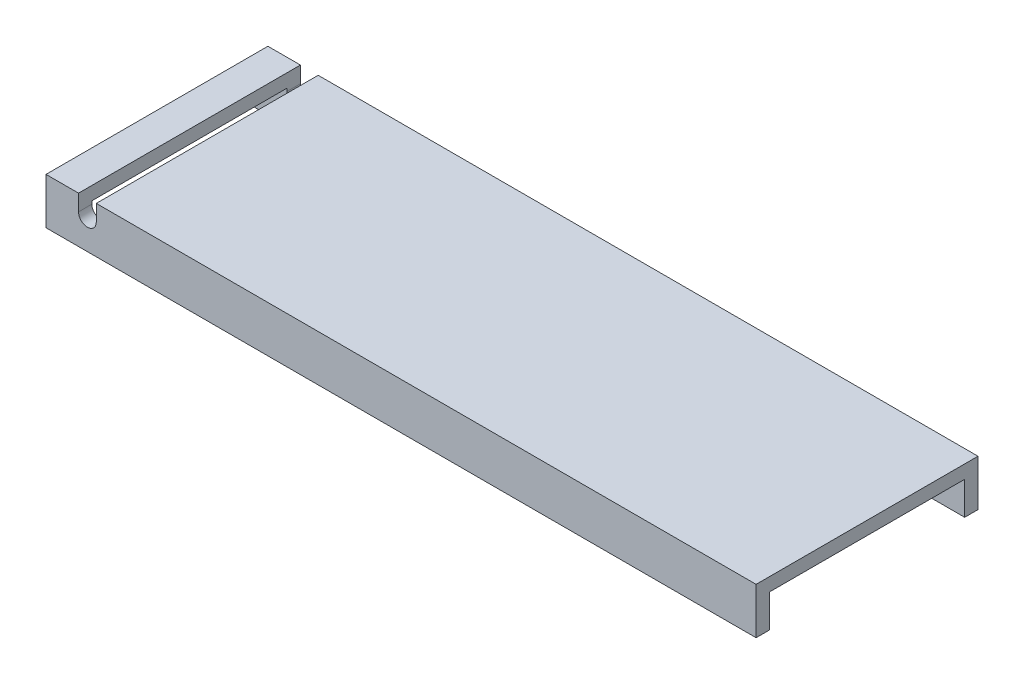
SolidWorks part; units mm, degrees
ref_plane "前视基准面" through (0, 0, 0) normal (0, 0, 1) x (1, 0, 0)
ref_plane "上视基准面" through (0, 0, 0) normal (0, 1, 0) x (1, 0, 0)
ref_plane "右视基准面" through (0, 0, 0) normal (1, 0, 0) x (0, 0, -1)
other "Configuration Table"
sketch "草图1" plane through (0, 0, 0) normal (1, 0, 0) x (0, 0, -1)
  line L0 (-11.391, 5.2124) -> (-11.391, -5.6876)
  line L1 (-9.891, 3.7124) -> (12.109, 3.7124)
  line L2 (-9.891, 3.7124) -> (-9.891, -4.1876)
  line L3 (-9.891, -4.1876) -> (12.109, -4.1876)
  line L4 (12.109, 3.7124) -> (12.109, -4.1876)
  line L5 (-9.891, 3.7124) -> (12.109, -4.1876) construction
  line L6 (-9.891, -4.1876) -> (12.109, 3.7124) construction
  line L7 (-11.391, -5.6876) -> (13.609, -5.6876)
  line L8 (13.609, 5.2124) -> (13.609, -5.6876)
  line L9 (-11.391, 5.2124) -> (13.609, 5.2124)
  point P0 (1.109, -0.2376)
  dimension "D1" = 7.9
  dimension "D2" = 22
  dimension "D3" = 1.5
extrude "凸台-拉伸1" add sketch "草图1" along normal blind 80
sketch "草图3" plane through (0, 0, 11.391) normal (0, 0, 1) x (1, 0, 0)
  line L0 (3.6643, 3.3873) -> (3.6643, 5.2124)
  line L1 (80, 5.2124) -> (0, 5.2124) construction
  line L2 (5.6643, 3.3873) -> (5.6643, 5.2124)
  line L3 (5.6643, 5.2124) -> (3.6643, 5.2124)
  line L5 (-3.2135, 0) -> (138.373, 0)
  line L6 (-3.2135, 0) -> (-3.2135, -11.0772)
  line L7 (-3.2135, -11.0772) -> (138.373, -11.0772)
  line L8 (138.373, 0) -> (138.373, -11.0772)
  arc A0 (3.6643, 3.3873) -> (5.6643, 3.3873) centre (4.6643, 3.3873) ccw
  point P1 (138.373, -11.0772)
  dimension "D1" = 2
extrude "切除-拉伸1" cut sketch "草图3" against normal blind 50
